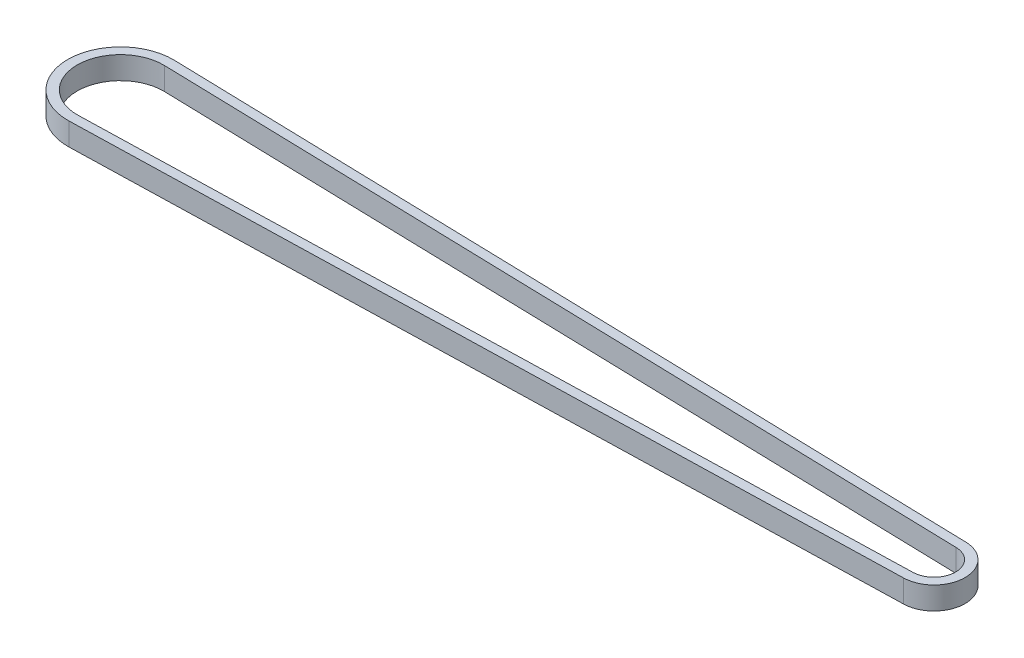
SolidWorks part; units mm, degrees
material "POLYURETHANE (11671)"
ref_plane "Front Plane" through (0, 0, 0) normal (0, 0, 1) x (1, 0, 0)
ref_plane "Top Plane" through (0, 0, 0) normal (0, 1, 0) x (1, 0, 0)
ref_plane "Right Plane" through (0, 0, 0) normal (1, 0, 0) x (0, 0, -1)
sketch "Sketch1" plane through (0, 0, 0) normal (0, 1, 0) x (1, 0, 0)
  line L0 (-107.95, 0) -> (107.95, 0) construction
  line L1 (0, 0) -> (0, 67523.6974) construction
  line L4 (-107.6462, 11.4514) -> (108.102, 5.727)
  line L5 (-107.6462, -11.4514) -> (108.102, -5.727)
  line L6 (0, 0) -> (0, 44.9411) construction
  line L7 (-107.5802, 13.9651) -> (108.1685, 8.2521)
  line L8 (-107.5802, -13.9651) -> (108.1685, -8.2521)
  arc A0 (-107.6462, 11.4514) -> (-107.6462, -11.4514) centre (-107.95, 0) ccw
  arc A1 (108.102, -5.727) -> (108.102, 5.727) centre (107.95, 0) ccw
  arc A2 (-107.5802, 13.9651) -> (-107.5802, -13.9651) centre (-107.95, 0) ccw
  arc A3 (108.1685, -8.2521) -> (108.1685, 8.2521) centre (107.95, 0) ccw
  dimension "D2" = 22.9108
  dimension "D3" = 11.4579
  dimension "D4" = 27.94
  dimension "D5" = 16.51
  dimension "D1" = 215.9
extrude "Boss-Extrude1" add sketch "Sketch1" along normal blind 5.9944
